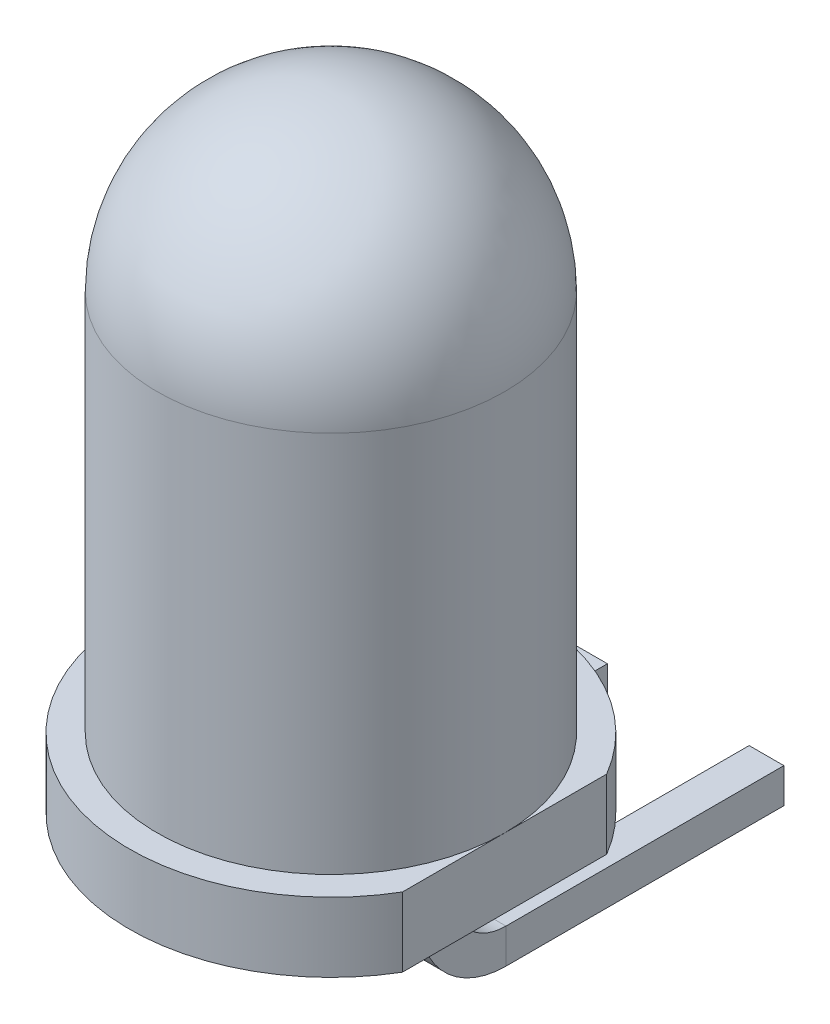
SolidWorks part; units mm, degrees
ref_plane "Front Plane" through (0, 0, 0) normal (0, 0, 1) x (1, 0, 0)
ref_plane "Top Plane" through (0, 0, 0) normal (0, 1, 0) x (1, 0, 0)
ref_plane "Right Plane" through (0, 0, 0) normal (1, 0, 0) x (0, 0, -1)
sketch "Sketch1" plane through (0, 0, 0) normal (0, 0, -1) x (1, 0, 0)
  line L0 (0, 0) -> (0, -9)
  line L1 (2.5, -6.5) -> (2.5, -1)
  line L2 (2.9, 0) -> (0, 0)
  line L3 (2.5, -1) -> (2.9, -1)
  line L4 (2.9, -1) -> (2.9, 0)
  arc A0 (2.5, -6.5) -> (0, -9) centre (0, -6.5) cw
  point P3 (0, -6.5348)
  dimension "D1" = 2.5
  dimension "D2" = 2.9
  dimension "D3" = 1
  dimension "D4" = 9
revolve "Revolve1" add sketch "Sketch1" angle 360 about L0
sketch "Sketch2" plane through (0, 0, 0) normal (0, -1, 0) x (-1, 0, 0)
  line L0 (-2.9, -1.4697) -> (-2.9, 1.4697)
  line L1 (-2.9, 1.4697) -> (-2.5, 1.4697)
  line L3 (-2.9, -1.4697) -> (-2.5, -1.4697)
  line L4 (-2.5, 1.4697) -> (-2.5, -1.4697)
  circle A1 centre (0, 0) radius 2.9 construction
  circle A2 centre (0, 0) radius 2.9 construction
  circle A3 centre (0, 0) radius 2.5 construction
extrude "Cut-Extrude1" cut sketch "Sketch2" against normal through all
sketch "Sketch3" plane through (0, 0, 0) normal (0, -1, 0) x (-1, 0, 0)
  line L0 (0, 1.7562) -> (0, 0) construction
  line L1 (0, 0) -> (1.27, 0) construction
  line L2 (-1.02, 0.25) -> (-1.02, -0.25)
  line L3 (1.02, 0.25) -> (1.52, 0.25)
  line L4 (1.02, 0.25) -> (1.02, -0.25)
  line L5 (1.02, -0.25) -> (1.52, -0.25)
  line L6 (1.52, 0.25) -> (1.52, -0.25)
  line L7 (1.02, 0.25) -> (1.52, -0.25) construction
  line L8 (1.02, -0.25) -> (1.52, 0.25) construction
  line L9 (-1.02, -0.25) -> (-1.52, -0.25)
  line L10 (-1.52, 0.25) -> (-1.52, -0.25)
  line L11 (-1.02, 0.25) -> (-1.52, 0.25)
  dimension "D1" = 0.5
  dimension "D2" = 1.27
ref_plane "Plane1" through (-1.27, 0, 0) normal (1, 0, 0) x (0, 0, -1)
sketch "Sketch4" plane through (-1.27, 0, 0) normal (1, 0, 0) x (0, 0, -1)
  line L0 (0, 0) -> (0, -0.4)
  line L1 (1, -1.4) -> (5, -1.4)
  arc A0 (0, -0.4) -> (1, -1.4) centre (1, -0.4) ccw
  dimension "D3" = 5
  dimension "D2" = 1
  dimension "D1" = 0.4
sweep "Sweep1" add profiles "Sketch3" path "Sketch4"
